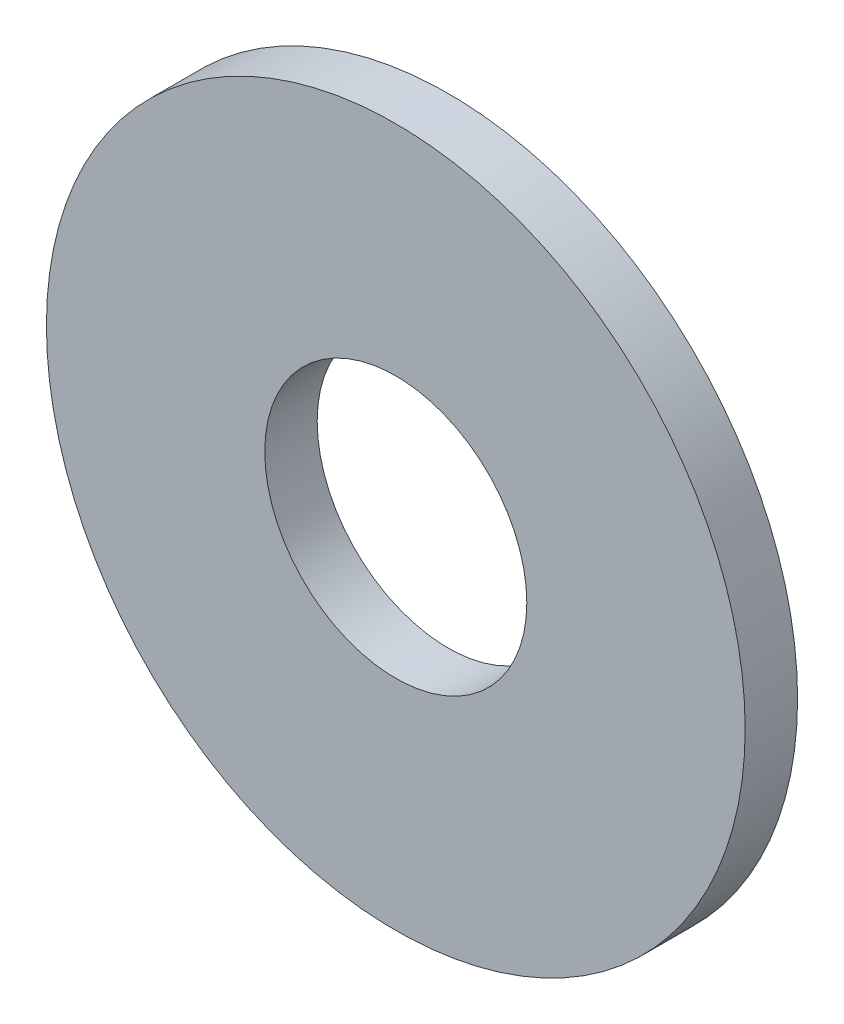
SolidWorks part; units mm, degrees
ref_plane "Front Plane" through (0, 0, 0) normal (0, 0, 1) x (1, 0, 0)
ref_plane "Top Plane" through (0, 0, 0) normal (0, 1, 0) x (1, 0, 0)
ref_plane "Right Plane" through (0, 0, 0) normal (1, 0, 0) x (0, 0, -1)
sketch "Sketch1" plane through (0, 0, 0) normal (0, 0, 1) x (1, 0, 0)
  circle A0 centre (0, 0) radius 15
  circle A1 centre (0, 0) radius 40
extrude "Boss-Extrude1" add sketch "Sketch1" along normal blind 6
